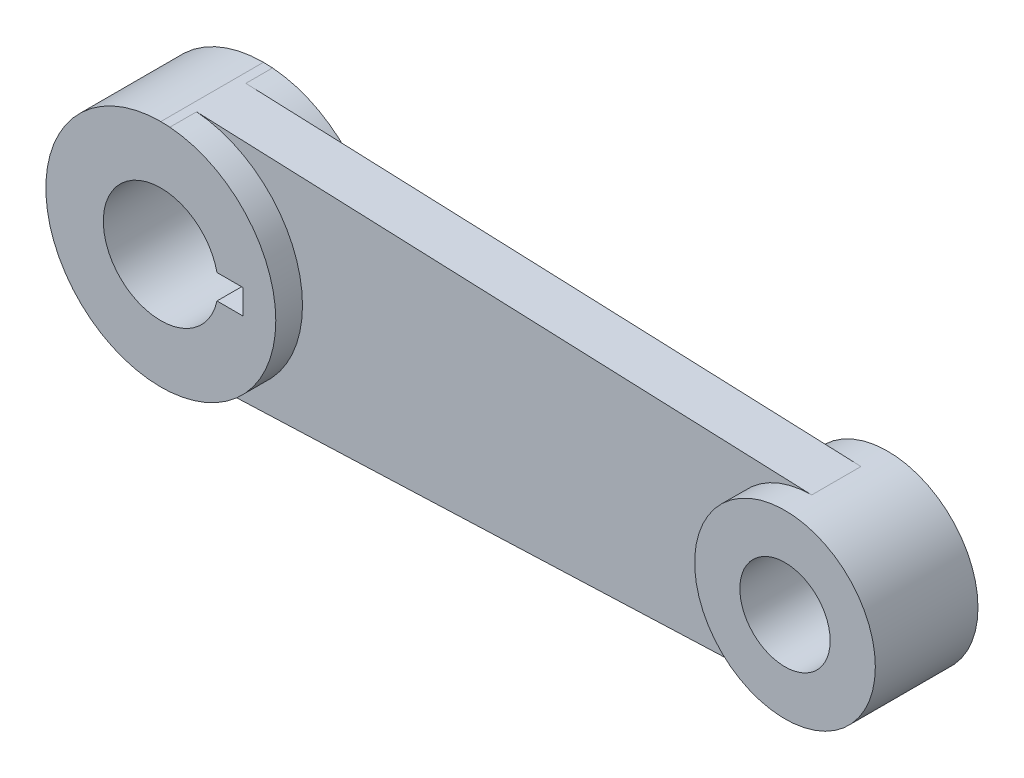
SolidWorks part; units mm, degrees
ref_plane "Front Plane" through (0, 0, 0) normal (0, 0, 1) x (1, 0, 0)
ref_plane "Top Plane" through (0, 0, 0) normal (0, 1, 0) x (1, 0, 0)
ref_plane "Right Plane" through (0, 0, 0) normal (1, 0, 0) x (0, 0, -1)
sketch "Sketch4" plane through (0, 0, 0) normal (0, 0, 1) x (1, 0, 0)
  line L0 (0, 14) -> (76, 11)
  line L1 (0, -14) -> (76, -11)
  line L2 (6.8374, 1.5) -> (10, 1.5)
  line L3 (10, 1.5) -> (10, -1.5)
  line L4 (10, -1.5) -> (6.8374, -1.5)
  line L5 (0, 0) -> (19.901, 0) construction
  arc A0 (6.8374, 1.5) -> (6.8374, -1.5) centre (0, 0) ccw
  circle A1 centre (0, 0) radius 14
  circle A2 centre (76, 0) radius 11
  circle A3 centre (76, 0) radius 5.5
  point P16 (10, 0)
  dimension "D1" = 14
  dimension "D2" = 14
  dimension "D3" = 11
  dimension "D4" = 11
  dimension "D5" = 76
  dimension "D6" = 3
  dimension "D7" = 10
extrude "Boss-Extrude3" add sketch "Sketch4" along normal mid plane 12.5
sketch "Sketch5" plane through (0, 0, 6.25) normal (0, 0, 1) x (1, 0, 0)
  line L0 (0, 14) -> (76, 11)
  line L1 (0, -14) -> (76, -11)
  arc A0 (0, -14) -> (0, 14) centre (0, 0) ccw
  arc A1 (76, 11) -> (76, -11) centre (76, 0) ccw
  line M3 (76, 11) -> (0, 14)
  dimension "D1" = 28
extrude "Cut-Extrude1" cut sketch "Sketch5" against normal blind 3.25 contours A1 A0 L1 M3
mirror "Mirror1" about plane through (0, 0, 0) normal (0, 0, 1) of "Cut-Extrude1"
